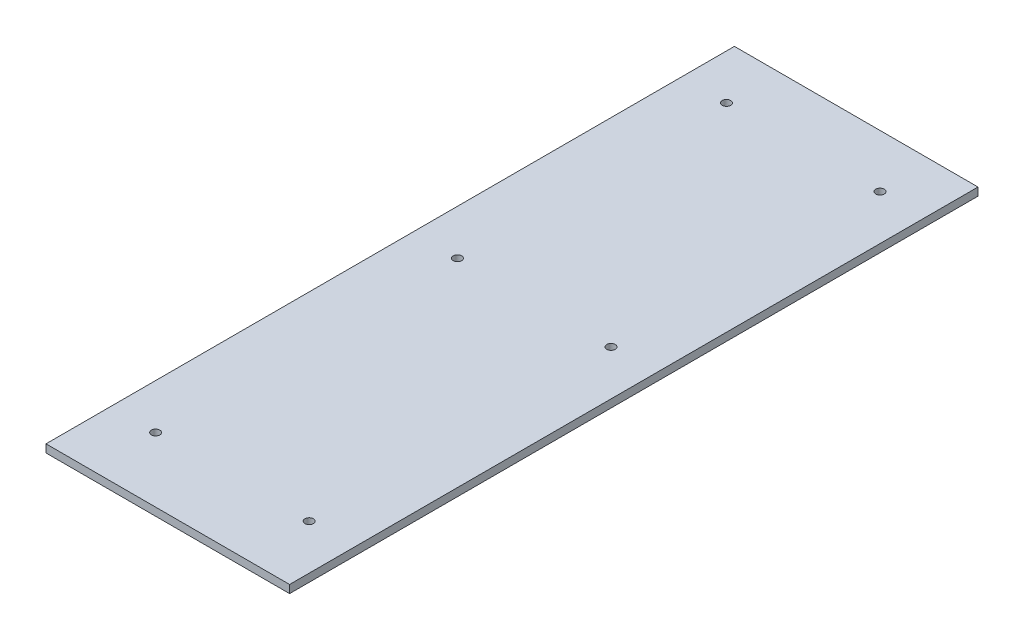
SolidWorks part; units mm, degrees
ref_plane "Plan de face" through (0, 0, 0) normal (0, 0, 1) x (1, 0, 0)
ref_plane "Plan de dessus" through (0, 0, 0) normal (0, 1, 0) x (1, 0, 0)
ref_plane "Plan de droite" through (0, 0, 0) normal (1, 0, 0) x (0, 0, -1)
sketch "Esquisse1" plane through (0, 0, 0) normal (0, 1, 0) x (1, 0, 0)
  line L1 (-34.9255, 37.0612) -> (57.0745, 37.0612)
  line L2 (-34.9255, 37.0612) -> (-34.9255, -222.9388)
  line L3 (-34.9255, -222.9388) -> (57.0745, -222.9388)
  line L4 (57.0745, 37.0612) -> (57.0745, -222.9388)
  dimension "D1" = 92
  dimension "D2" = 260
extrude "Boss.-Extru.1" add sketch "Esquisse1" along normal blind 3 contours L1 L4 L3 L2
sketch "Esquisse2" plane through (0, 3, 0) normal (0, 1, 0) x (1, 0, 0)
  line L0 (-34.9255, -222.9388) -> (57.0745, -222.9388) construction
  line L2 (-34.9255, 37.0612) -> (-34.9255, -222.9388) construction
  line L3 (-34.9255, 37.0612) -> (57.0745, 37.0612) construction
  circle A0 centre (-17.9255, -198.5388) radius 1.6
  circle A1 centre (40.0745, -198.5388) radius 1.6
  circle A2 centre (-17.9255, -84.5388) radius 1.6
  circle A3 centre (40.0745, -84.5388) radius 1.6
  circle A4 centre (-17.9255, 17.0612) radius 1.6
  circle A5 centre (40.0745, 17.0612) radius 1.6
  dimension "D3" = 3.2
  dimension "D4" = 3.2
  dimension "D9" = 3.2
  dimension "D10" = 3.2
  dimension "D17" = 3.2
  dimension "D18" = 3.2
  dimension "D1" = 24.4
  dimension "D2" = 24.4
  dimension "D5" = 58
  dimension "D6" = 17
  dimension "D7" = 114
  dimension "D8" = 114
  dimension "D11" = 58
  dimension "D12" = 17
  dimension "D13" = 20
  dimension "D14" = 20
  dimension "D15" = 58
  dimension "D16" = 17
extrude "Enlèv. mat.-Extru.1" cut sketch "Esquisse2" against normal up to next
equation "\"D1@Esquisse2\"=10.4+14"
equation "\"D5@Esquisse2\"=80-22"
equation "\"D6@Esquisse2\"=(92-58)/2"
equation "\"D7@Esquisse2\"=142-14-14"
equation "\"D13@Esquisse2\"=6+14"
